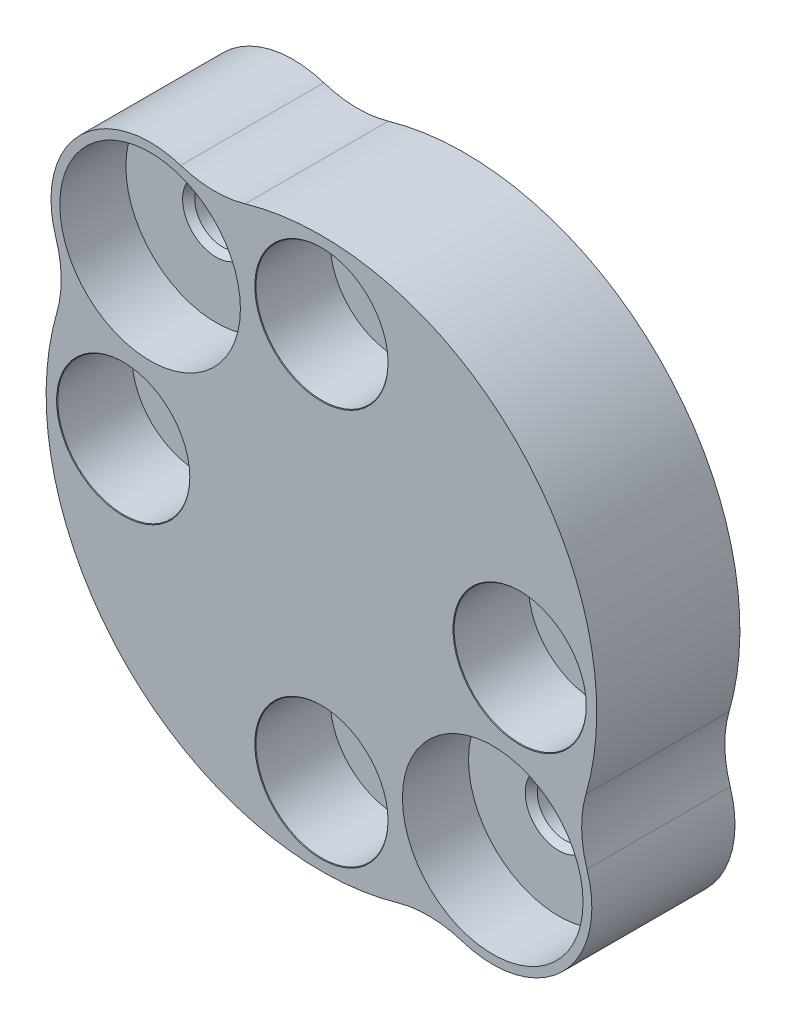
SolidWorks part; units mm, degrees
material "6061 Alloy"
ref_plane "Front Plane" through (0, 0, 0) normal (0, 0, 1) x (1, 0, 0)
ref_plane "Top Plane" through (0, 0, 0) normal (0, 1, 0) x (1, 0, 0)
ref_plane "Right Plane" through (0, 0, 0) normal (1, 0, 0) x (0, 0, -1)
sketch "Sketch1" plane through (0, 0, 0) normal (0, 0, 1) x (1, 0, 0)
  circle A0 centre (0, 0) radius 12.5
  dimension "D1" = 25
extrude "Boss-Extrude1" add sketch "Sketch1" along normal blind 6.5 contours A0
sketch "Sketch2" plane through (0, 0, 6.5) normal (0, 0, 1) x (1, 0, 0)
  point P0 (-9, 0)
  dimension "D1" = 9
sketch "Sketch5" plane through (0, 0, 6.5) normal (0, 0, 1) x (1, 0, 0)
  line L0 (-7.7782, 7.7782) -> (0, 0) construction
  line L4 (55, 0) -> (-55, 0) construction
  circle A5 centre (-7.7782, 7.7782) radius 4.5
  dimension "D2" = 11
  dimension "D3" = 9
  dimension "D1" = 45
hole_wizard "CBORE for M3 Hexagon socket head cap screws1" positions "3DSketch1" profile "Sketch4" counterbore size "M3" standard "GB" end condition through all
sketch3d "3DSketch1"
  point P0 (-9, 0, 6.5)
sketch "Sketch4" plane through (-9, 0, 6.5) normal (1, 0, 0) x (0, -1, 0)
  line L0 (0, 0) -> (0, 6.5)
  line L1 (0, 6.5) -> (1.6, 6.5)
  line L3 (1.6, 6.5) -> (1.6, 3.4)
  line L4 (3, 3.4) -> (1.6, 3.4)
  line L5 (3, 3.4) -> (3, 0.025)
  line L6 (3, 0.025) -> (3.025, 0)
  line L7 (3.025, 0) -> (0, 0)
  line L8 (-3, 0.025) -> (-3.025, 0) construction
  line L11 (0, -6.35) -> (0, 107.95) construction
  dimension "Thru Hole Dia." = 3.2
  dimension "Thru Hole Depth" = 6.5
  dimension "C'Bore Dia." = 6
  dimension "C'Bore Depth" = 3.4
  dimension "Near C'Sink Dia." = 6.05
  dimension "Near C'Sink Angle" = 90
pattern_circular "CirPattern1" count 4 every 90 about axis through (0, 0, 0) along (0, 0, 1) of "CBORE for M3 Hexagon socket head cap screws1"
extrude "Boss-Extrude3" add sketch "Sketch5" against normal up to surface (6.5 mm away) up to face at (1.6, -9, 0)
sketch "Sketch7" plane through (0, 0, 6.5) normal (0, 0, 1) x (1, 0, 0)
  circle A0 centre (-7.7782, 7.7782) radius 4.1
  arc A7 (-5.115, 11.4055) -> (-11.4055, 5.115) centre (-7.7782, 7.7782) ccw construction
  dimension "D1" = 8.2
extrude "Cut-Extrude2" cut sketch "Sketch7" against normal blind 3
pattern_circular "CirPattern3" count 2 every 180 about axis through (0, 0, 0) along (0, 0, 1) of "Boss-Extrude3", "Cut-Extrude2"
fillet "Fillet2" radius 5 4 edges at (5.115, -11.4055, 3.25) (11.4055, -5.115, 3.25) (-5.115, 11.4055, 3.25) (-11.4055, 5.115, 3.25)
sketch "Sketch8" plane through (0, 0, 3.5) normal (0, 0, 1) x (1, 0, 0)
  circle A0 centre (7.7782, -7.7782) radius 4.1 construction
  circle A1 centre (-7.7782, 7.7782) radius 4.1 construction
  point P0 (-7.7782, 7.7782)
  point P1 (7.7782, -7.7782)
hole_wizard "M3 Tapped Hole1" positions "3DSketch2" profile "Sketch10" tap size "M3" standard "GB" end condition through all
sketch3d "3DSketch2"
  point P0 (-7.7782, 7.7782, 3.5)
  point P3 (7.7782, -7.7782, 3.5)
sketch "Sketch10" plane through (-7.7782, 7.7782, 3.5) normal (1, 0, 0) x (0, -1, 0)
  line L0 (0, 0) -> (0, 3.5)
  line L1 (0, 3.5) -> (1.25, 3.5)
  line L2 (1.25, 3.5) -> (1.25, 0.275)
  line L3 (1.25, 0.275) -> (1.525, 0)
  line L5 (1.525, 0) -> (0, 0)
  line L6 (-1.25, 0.275) -> (-1.525, 0) construction
  line L11 (0, -6.35) -> (0, 107.95) construction
  dimension "Thru Tap Drill Dia." = 2.5
  dimension "Thru Tap Drill Depth" = 3.5
  dimension "Near C'Sink Dia." = 3.05
  dimension "Near C'Sink Angle" = 90
